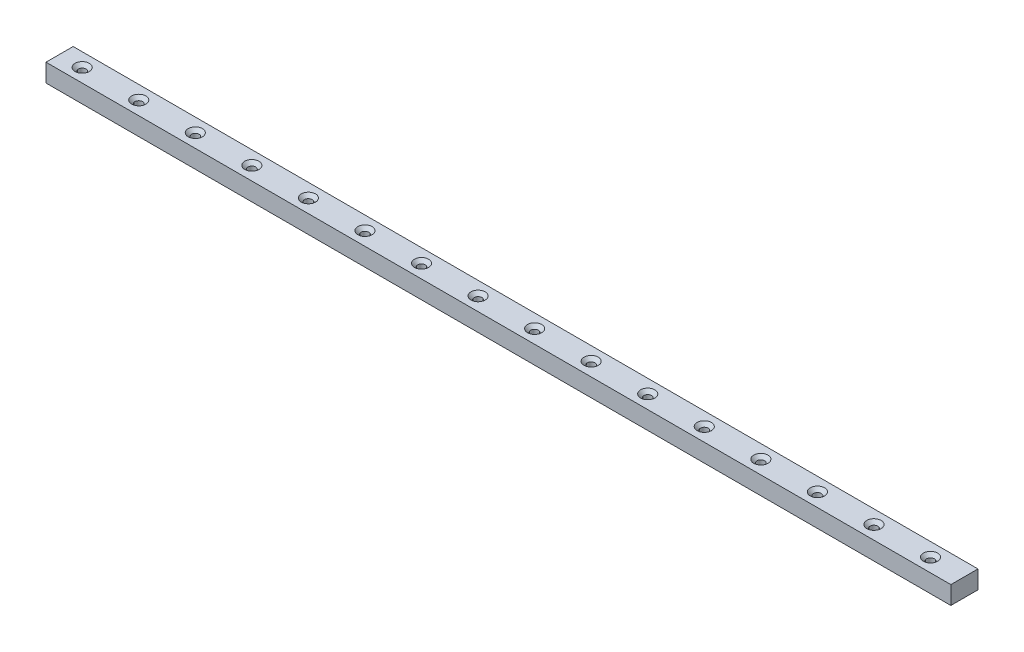
SolidWorks part; units mm, degrees
ref_plane "Front Plane" through (0, 0, 0) normal (0, 0, 1) x (1, 0, 0)
ref_plane "Top Plane" through (0, 0, 0) normal (0, 1, 0) x (1, 0, 0)
ref_plane "Right Plane" through (0, 0, 0) normal (1, 0, 0) x (0, 0, -1)
sketch "Sketch1" plane through (0, 0, 0) normal (1, 0, 0) x (0, 0, -1)
  line L1 (-6, -4) -> (6, -4)
  line L2 (-6, -4) -> (-6, 4)
  line L3 (-6, 4) -> (6, 4)
  line L4 (6, -4) -> (6, 4)
  line L5 (-6, -4) -> (6, 4) construction
  line L6 (-6, 4) -> (6, -4) construction
  point P0 (0, 0)
  dimension "D1" = 12
  dimension "D2" = 8
extrude "Boss-Extrude1" add sketch "Sketch1" along normal blind 400 contours L3 L4 L1 L2
hole_wizard "CSK for M3 Flat Head Machine Screw1" positions "Sketch4" profile "Sketch3" countersink size "M3" standard "ANSI Metric" end condition through all
sketch "Sketch4" plane through (0, 4, 0) normal (0, 1, 0) x (1, 0, 0)
  line L0 (400, 6) -> (0, 6) construction
  point P0 (10, 0)
  dimension "D1" = 10
  dimension "D2" = 6
sketch "Sketch3" plane through (10, 4, 0) normal (1, 0, 0) x (0, 0, 1)
  line L0 (0, 0) -> (0, 8)
  line L1 (0, 8) -> (1.7, 8)
  line L2 (1.7, 8) -> (1.7, 1.45)
  line L3 (1.7, 1.45) -> (3.15, 0)
  line L5 (3.15, 0) -> (0, 0)
  line L6 (-1.7, 1.45) -> (-3.15, 0) construction
  line L11 (0, -6.35) -> (0, 107.95) construction
  dimension "Thru Hole Dia." = 3.4
  dimension "Thru Hole Depth" = 8
  dimension "Near C'Sink Dia." = 6.3
  dimension "Near C'Sink Angle" = 90
pattern_linear "LPattern1" count 16 spacing 25 along (1, 0, 0) of "CSK for M3 Flat Head Machine Screw1"
